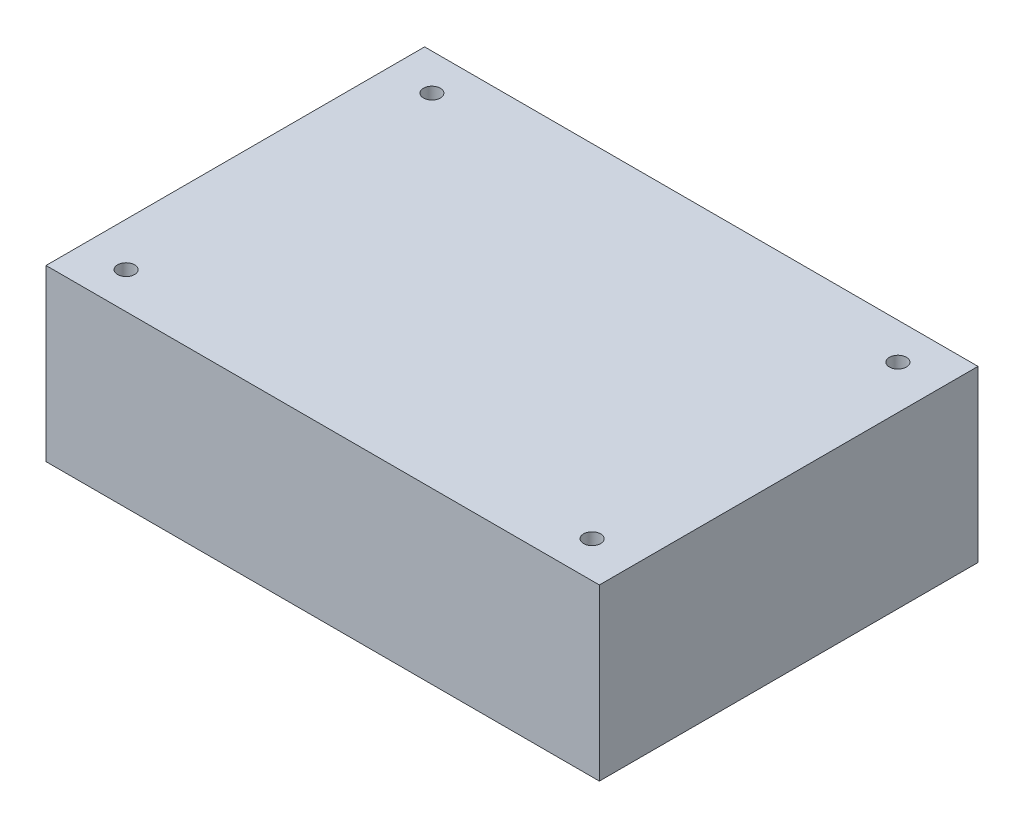
SolidWorks part; units mm, degrees
ref_plane "前视基准面" through (0, 0, 0) normal (0, 0, 1) x (1, 0, 0)
ref_plane "上视基准面" through (0, 0, 0) normal (0, 1, 0) x (1, 0, 0)
ref_plane "右视基准面" through (0, 0, 0) normal (1, 0, 0) x (0, 0, -1)
sketch "草图1" plane through (0, 0, 0) normal (0, 1, 0) x (1, 0, 0)
  line L1 (-57, -39) -> (57, -39)
  line L2 (-57, -39) -> (-57, 39)
  line L3 (-57, 39) -> (57, 39)
  line L4 (57, -39) -> (57, 39)
  line L5 (-57, -39) -> (57, 39) construction
  line L6 (-57, 39) -> (57, -39) construction
  line L7 (-48, -31.5) -> (48, -31.5) construction
  line L8 (-48, -31.5) -> (-48, 31.5) construction
  line L9 (-48, 31.5) -> (48, 31.5) construction
  line L10 (48, -31.5) -> (48, 31.5) construction
  line L11 (-48, -31.5) -> (48, 31.5) construction
  line L12 (-48, 31.5) -> (48, -31.5) construction
  circle A0 centre (-48, 31.5) radius 1.75
  circle A1 centre (-48, -31.5) radius 1.75
  circle A2 centre (48, -31.5) radius 1.75
  circle A3 centre (48, 31.5) radius 1.75
  point P0 (0, 0)
  point P6 (0, 0)
  dimension "D5" = 3.5
  dimension "D1" = 78
  dimension "D2" = 114
  dimension "D3" = 96
  dimension "D4" = 63
extrude "凸台-拉伸1" add sketch "草图1" along normal blind 35
